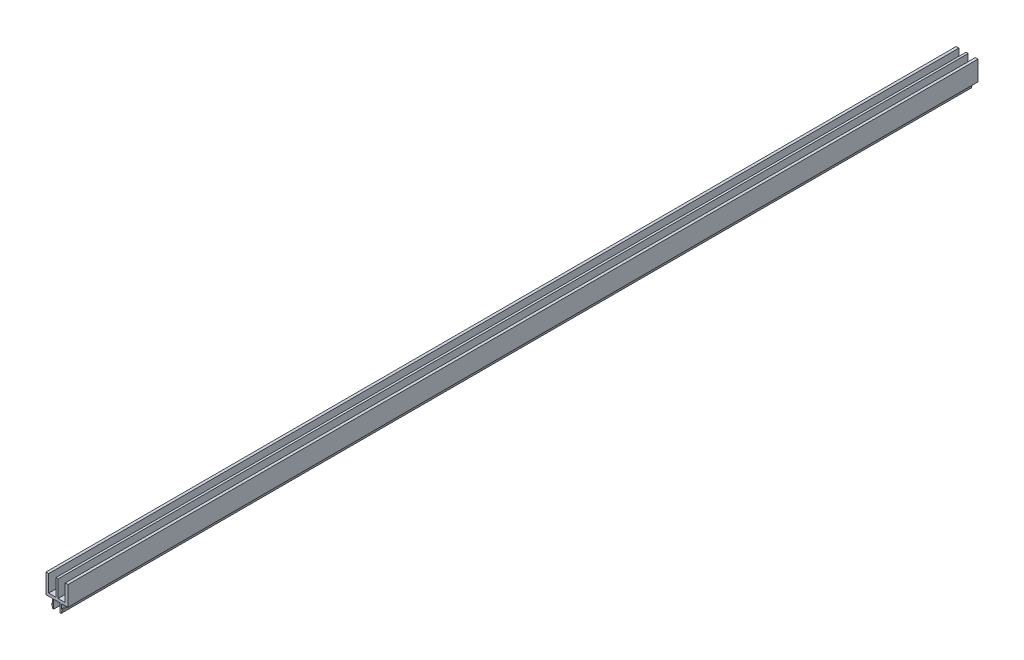
SolidWorks part; units mm, degrees
ref_plane "Plan de face" through (0, 0, 0) normal (0, 0, 1) x (1, 0, 0)
ref_plane "Plan de dessus" through (0, 0, 0) normal (0, 1, 0) x (1, 0, 0)
ref_plane "Plan de droite" through (0, 0, 0) normal (1, 0, 0) x (0, 0, -1)
ref_plane "Plan1" through (0, 0, 50) normal (0, 0, 1) x (1, 0, 0)
sketch "Esquisse1" plane through (0, 0, 50) normal (0, 0, 1) x (1, 0, 0)
  line L0 (-1, 2.5) -> (-7.5, 2.5)
  line L1 (-7.5, 2.5) -> (-7.5, 18)
  line L2 (-7.5, 18) -> (-10, 18)
  line L3 (-10, 18) -> (-10, 0)
  line L4 (-10, 0) -> (-4, 0)
  line L5 (-4, 0) -> (-4, -4.5)
  line L6 (-4, -4.5) -> (-5, -4.5)
  line L7 (-5, -4.5) -> (-3.75, -8)
  line L8 (-3.75, -8) -> (-3, -8)
  line L9 (-3, -8) -> (-3, 0)
  line L10 (-3, 0) -> (3, 0)
  line L11 (3, 0) -> (3, -8)
  line L12 (3, -8) -> (3.75, -8)
  line L13 (3.75, -8) -> (5, -4.5)
  line L14 (5, -4.5) -> (4, -4.5)
  line L15 (4, -4.5) -> (4, 0)
  line L16 (4, 0) -> (10, 0)
  line L17 (10, 0) -> (10, 18)
  line L18 (10, 18) -> (7.5, 18)
  line L19 (7.5, 18) -> (7.5, 2.5)
  line L20 (7.5, 2.5) -> (1, 2.5)
  line L21 (1, 2.5) -> (1, 18)
  line L22 (1, 18) -> (-1, 18)
  line L23 (-1, 18) -> (-1, 2.5)
extrude "Boss.-Extru.1" add sketch "Esquisse1" against normal blind 832
